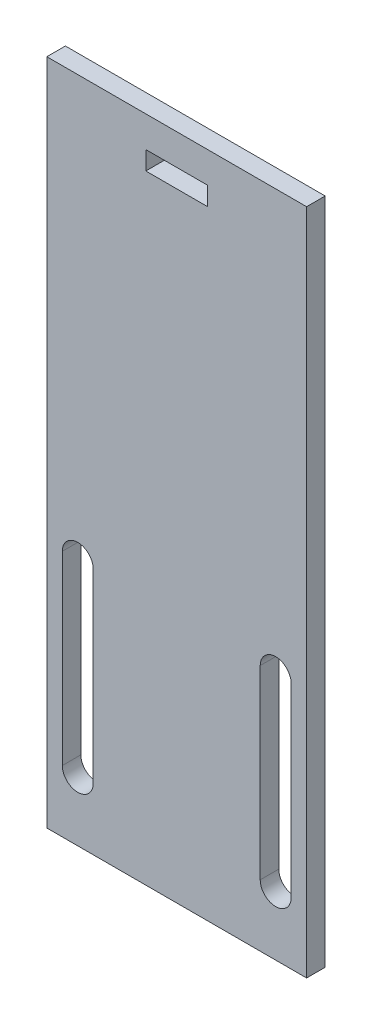
SolidWorks part; units mm, degrees
ref_plane "Front Plane" through (0, 0, 0) normal (0, 0, 1) x (1, 0, 0)
ref_plane "Top Plane" through (0, 0, 0) normal (0, 1, 0) x (1, 0, 0)
ref_plane "Right Plane" through (0, 0, 0) normal (1, 0, 0) x (0, 0, -1)
sketch "Sketch1" plane through (0, 0, 0) normal (0, 0, 1) x (1, 0, 0)
  line L0 (-13.5, -38.9099) -> (-13.5, -68.9099)
  line L1 (21, -78.9099) -> (-21, -78.9099)
  line L2 (21, -78.9099) -> (21, 29.0901)
  line L3 (21, 29.0901) -> (-5, 29.0901)
  line L4 (-21, -78.9099) -> (-21, 29.0901)
  line L7 (-18.5, -38.9099) -> (-18.5, -68.9099)
  line L8 (18.5, -38.9099) -> (18.5, -68.9099)
  line L9 (13.5, -38.9099) -> (13.5, -68.9099)
  line L11 (-5, 29.0901) -> (-21, 29.0901)
  line L12 (0, 29.0901) -> (0, 0) construction
  line L14 (5, 24.0901) -> (-5, 24.0901)
  line L15 (5, 24.0901) -> (5, 21.0901)
  line L16 (5, 21.0901) -> (-5, 21.0901)
  line L17 (-5, 24.0901) -> (-5, 21.0901)
  line L18 (5, 24.0901) -> (-5, 21.0901) construction
  line L19 (5, 21.0901) -> (-5, 24.0901) construction
  arc A0 (-18.5, -68.9099) -> (-13.5, -68.9099) centre (-16, -68.9099) ccw
  arc A1 (13.5, -68.9099) -> (18.5, -68.9099) centre (16, -68.9099) ccw
  arc A2 (18.5, -38.9099) -> (13.5, -38.9099) centre (16, -38.9099) ccw
  arc A3 (-13.5, -38.9099) -> (-18.5, -38.9099) centre (-16, -38.9099) ccw
  point P0 (0, 0)
  point P13 (0, 22.5901)
  dimension "D3" = 5
  dimension "D9" = 3
  dimension "D1" = 42
  dimension "D2" = 100
  dimension "D4" = 30
  dimension "D5" = 30
  dimension "D6" = 5
  dimension "D7" = 5
  dimension "D8" = 5
  dimension "D10" = 10
  dimension "D11" = 16
  dimension "D12" = 5
  dimension "10" = 10
extrude "Boss-Extrude1" add sketch "Sketch1" along normal blind 3
